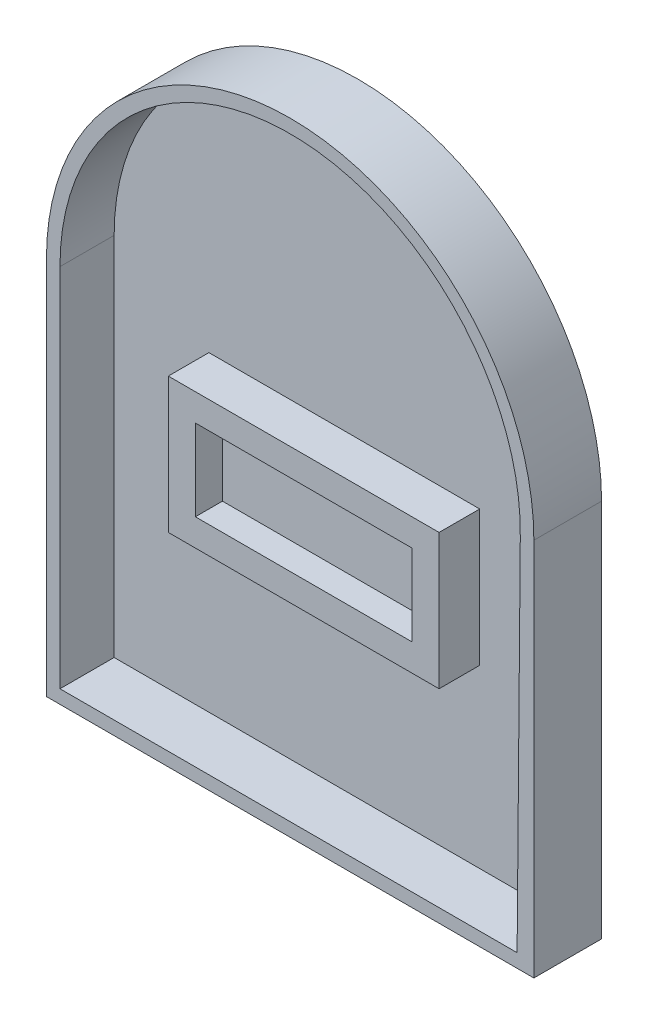
SolidWorks part; units mm, degrees
ref_plane "Front Plane" through (0, 0, 0) normal (0, 0, 1) x (1, 0, 0)
ref_plane "Top Plane" through (0, 0, 0) normal (0, 1, 0) x (1, 0, 0)
ref_plane "Right Plane" through (0, 0, 0) normal (1, 0, 0) x (0, 0, -1)
sketch "Sketch1" plane through (0, 0, 0) normal (0, 0, 1) x (1, 0, 0)
  line L0 (0, 0) -> (0, -158.6427) construction
  line L1 (-90, 0) -> (-90, -140)
  line L2 (-90, -140) -> (90, -140)
  line L3 (90, -140) -> (90, 0)
  line L4 (-85, 0) -> (-85, -135)
  line L5 (-85, -135) -> (83.8115, -135)
  line L6 (83.8115, -135) -> (84.9868, -1.4965)
  arc A0 (90, 0) -> (-90, 0) centre (0, 0) ccw
  arc A1 (84.9868, -1.4965) -> (-85, 0) centre (0, 0) ccw
  dimension "D1" = 180
  dimension "D3" = 170
  dimension "D2" = 140
  dimension "D4" = 83.8115
  dimension "D5" = 84.9868
  dimension "D6" = 135
extrude "Boss-Extrude1" add sketch "Sketch1" along normal blind 20
sketch "Sketch2" plane through (0, 0, 0) normal (0, 0, -1) x (-1, 0, 0)
  line L3 (-90, 0) -> (-90, -140)
  line L4 (-90, -140) -> (90, -140)
  line L5 (90, -140) -> (90, 0)
  line L6 (-90, 0) -> (-90, -140)
  line L7 (-90, -140) -> (90, -140)
  line L8 (90, -140) -> (90, 0)
  arc A1 (90, 0) -> (-90, 0) centre (0, 0) ccw
  arc A2 (90, 0) -> (-90, 0) centre (0, 0) ccw
  dimension "D1" = 0
extrude "Boss-Extrude2" add sketch "Sketch2" along normal blind 5
sketch "Sketch3" plane through (0, 0, 0) normal (0, 0, 1) x (1, 0, 0)
  line L1 (-50, -20) -> (50, -20)
  line L2 (-50, -20) -> (-50, -70)
  line L3 (-50, -70) -> (50, -70)
  line L4 (50, -20) -> (50, -70)
  line L5 (-50, -20) -> (50, -70) construction
  line L6 (-50, -70) -> (50, -20) construction
  point P0 (0, -45)
  point P5 (0, -20)
  dimension "D1" = 100
  dimension "D2" = 50
  dimension "D3" = 20
extrude "Boss-Extrude3" add sketch "Sketch3" along normal blind 15
shell "Shell1" thickness 10
